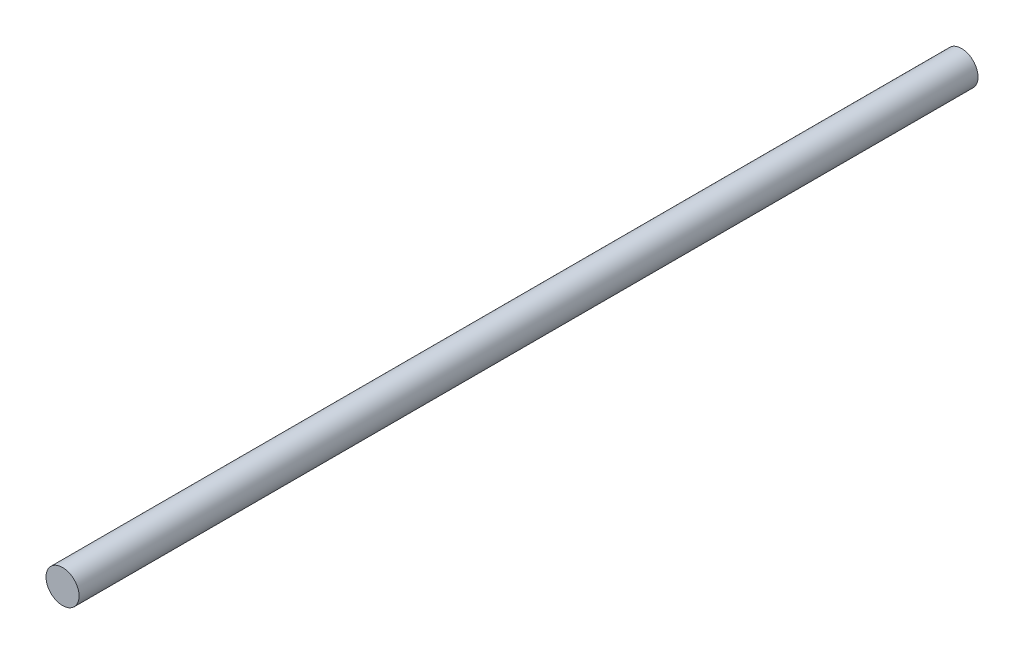
SolidWorks part; units mm, degrees
ref_plane "Front Plane" through (0, 0, 0) normal (0, 0, 1) x (1, 0, 0)
ref_plane "Top Plane" through (0, 0, 0) normal (0, 1, 0) x (1, 0, 0)
ref_plane "Right Plane" through (0, 0, 0) normal (1, 0, 0) x (0, 0, -1)
sketch "Sketch1" plane through (0, 0, 0) normal (0, 0, 1) x (1, 0, 0)
  circle A0 centre (0, 0) radius 4
  dimension "D1" = 8
extrude "Boss-Extrude1" add sketch "Sketch1" along normal blind 217.5
scale "Scale1" scale about centroid uniform scaling yes scale factor 10
